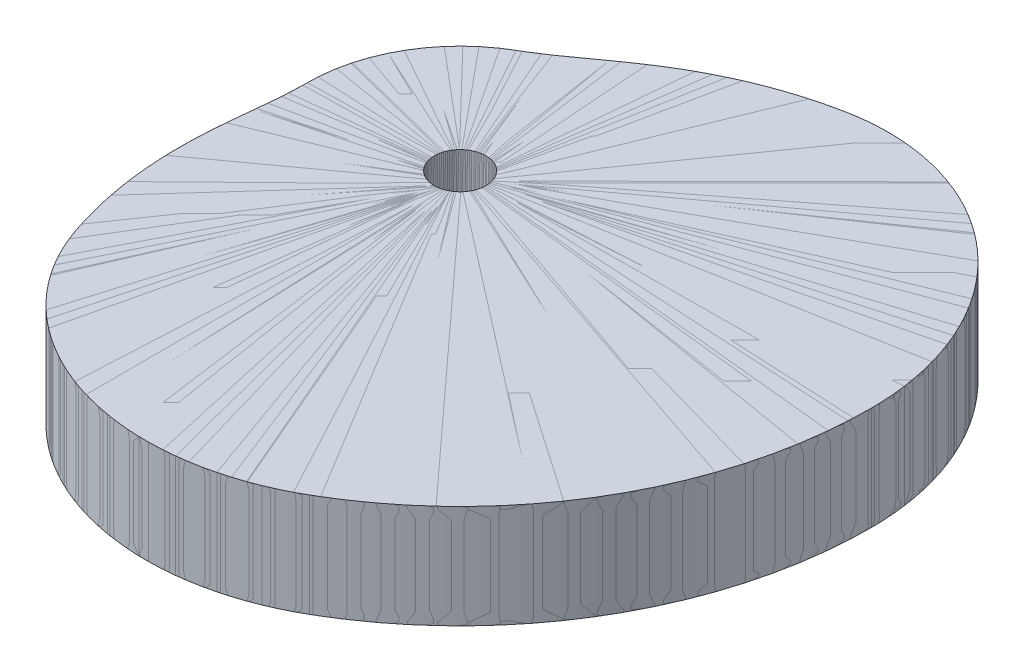
SolidWorks part; units mm, degrees
ref_plane "前视基准面" through (0, 0, 0) normal (0, 0, 1) x (1, 0, 0)
ref_plane "上视基准面" through (0, 0, 0) normal (0, 1, 0) x (1, 0, 0)
ref_plane "右视基准面" through (0, 0, 0) normal (1, 0, 0) x (0, 0, -1)
other "质心 (COM)"
other "Configuration Table"
sketch "草图1" plane through (0, 0, 0) normal (0, 0, 1) x (1, 0, 0)
  line L0 (0, -20200) -> (0, 200) construction
  line L1 (5, 0) -> (80, 0)
  line L2 (80, 0) -> (80, -20)
  line L3 (80, -20) -> (5, -20)
  line L4 (5, -20) -> (5, 0)
revolve "旋转1" add sketch "草图1" angle 360 about L0
sketch "草图2" plane through (0, 0, 0) normal (0, 1, 0) x (1, 0, 0)
  line L0 (0, 0) -> (80, 0) construction
  arc A0 (79.5, 0) -> (79.027, 6.889) centre (29.0158, -0.0054) ccw
  arc A1 (79.027, 6.889) -> (77.6192, 13.6356) centre (29.3188, 0.0363) ccw
  arc A2 (77.6192, 13.6356) -> (75.3065, 20.1004) centre (29.7814, 0.1687) ccw
  arc A3 (75.3065, 20.1004) -> (72.1392, 26.149) centre (30.4291, 0.4546) ccw
  arc A4 (72.1392, 26.149) -> (68.1863, 31.6554) centre (31.21, 0.9379) ccw
  arc A5 (68.1863, 31.6554) -> (63.5342, 36.5035) centre (32.0595, 1.6461) ccw
  arc A6 (63.5342, 36.5035) -> (58.286, 40.5905) centre (32.9058, 2.5861) ccw
  arc A7 (58.286, 40.5905) -> (52.559, 43.8282) centre (33.6758, 3.7418) ccw
  arc A8 (52.559, 43.8282) -> (46.4828, 46.1451) centre (34.3014, 5.073) ccw
  arc A9 (46.4828, 46.1451) -> (40.1976, 47.4881) centre (34.7286, 6.5165) ccw
  arc A10 (40.1976, 47.4881) -> (33.8508, 47.8241) centre (34.9248, 7.9896) ccw
  arc A11 (33.8508, 47.8241) -> (27.59, 47.1393) centre (34.8892, 9.3651) ccw
  arc A12 (27.59, 47.1393) -> (21.6911, 45.7463) centre (41.7163, -25.8693) ccw
  arc A13 (21.6911, 45.7463) -> (16.3696, 44.035) centre (41.2849, -24.3103) ccw
  arc A14 (16.3696, 44.035) -> (11.6082, 42.1045) centre (41.16, -23.9463) ccw
  arc A15 (11.6082, 42.1045) -> (7.3715, 40.0439) centre (41.8148, -25.3862) ccw
  arc A16 (7.3715, 40.0439) -> (3.6125, 37.9311) centre (44.1291, -29.7547) ccw
  arc A17 (3.6125, 37.9311) -> (0.2748, 35.8322) centre (50.161, -39.7958) ccw
  arc A18 (0.2748, 35.8322) -> (-2.7058, 33.8002) centre (66.4018, -64.3674) ccw
  arc A19 (-2.7058, 33.8002) -> (-5.3989, 31.8746) centre (130.8056, -155.763) ccw
  arc A20 (-5.3989, 31.8746) -> (-7.8774, 30.0809) centre (-573.3815, 814.0785) cw
  arc A21 (-7.8774, 30.0809) -> (-10.2149, 28.4313) centre (-88.8574, 142.3512) cw
  arc A22 (-10.2149, 28.4313) -> (-12.4833, 26.9248) centre (-53.86, 91.691) cw
  arc A23 (-12.4833, 26.9248) -> (-14.75, 25.5477) centre (-44.8377, 77.6266) cw
  arc A24 (-14.75, 25.5477) -> (-29.5, 0) centre (0, 0) ccw
  arc A25 (-29.5, 0) -> (-29.5592, -2.6515) centre (-89.6454, 0.0173) cw
  arc A26 (-29.5592, -2.6515) -> (-29.7297, -5.3693) centre (-106.3368, 0.7987) cw
  arc A27 (-29.7297, -5.3693) -> (-29.9895, -8.2184) centre (-167.7085, 5.7772) cw
  arc A28 (-29.9895, -8.2184) -> (-30.3036, -11.2617) centre (-991.7034, 89.5237) cw
  arc A29 (-30.3036, -11.2617) -> (-30.6248, -14.5568) centre (200.2976, -35.3995) ccw
  arc A30 (-30.6248, -14.5568) -> (-30.8942, -18.1541) centre (88.9447, -25.3219) ccw
  arc A31 (-30.8942, -18.1541) -> (-31.0431, -22.0941) centre (59.5447, -23.5428) ccw
  arc A32 (-31.0431, -22.0941) -> (-30.9933, -26.4058) centre (47.8328, -23.3396) ccw
  arc A33 (-30.9933, -26.4058) -> (-30.6595, -31.1053) centre (42.8925, -23.5195) ccw
  arc A34 (-30.6595, -31.1053) -> (-29.9506, -36.194) centre (41.3181, -23.6724) ccw
  arc A35 (-29.9506, -36.194) -> (-28.772, -41.6582) centre (41.6958, -23.5986) ccw
  arc A36 (-28.772, -41.6582) -> (-27.0288, -47.4633) centre (43.2617, -23.1927) ccw
  arc A37 (-27.0288, -47.4633) -> (-24.4914, -53.2277) centre (9.3342, -34.8975) ccw
  arc A38 (-24.4914, -53.2277) -> (-21.0271, -58.5562) centre (10.5432, -34.2405) ccw
  arc A39 (-21.0271, -58.5562) -> (-16.7214, -63.3279) centre (11.7208, -33.3341) ccw
  arc A40 (-16.7214, -63.3279) -> (-11.6768, -67.4315) centre (12.7573, -32.2424) ccw
  arc A41 (-11.6768, -67.4315) -> (-6.0094, -70.7724) centre (13.5974, -31.035) ccw
  arc A42 (-6.0094, -70.7724) -> (0.1541, -73.274) centre (14.2133, -29.7903) ccw
  arc A43 (0.1541, -73.274) -> (6.6788, -74.8787) centre (14.6042, -28.5873) ccw
  arc A44 (6.6788, -74.8787) -> (13.4239, -75.5489) centre (14.7927, -27.4976) ccw
  arc A45 (13.4239, -75.5489) -> (20.2458, -75.2676) centre (14.8209, -26.5797) ccw
  arc A46 (20.2458, -75.2676) -> (27.0008, -74.038) centre (14.7446, -25.8758) ccw
  arc A47 (27.0008, -74.038) -> (33.5475, -71.8839) centre (14.6279, -25.409) ccw
  arc A48 (33.5475, -71.8839) -> (39.75, -68.849) centre (14.5126, -25.1257) ccw
  arc A49 (39.75, -68.849) -> (79.5, 0) centre (0, 0) ccw
extrude "切除-拉伸1" cut sketch "草图2" along normal blind 10 and the other way blind 30 flip side to cut
sketch "草图3" plane through (0, 0, 0) normal (0, 1, 0) x (1, 0, 0)
  circle A0 centre (0, 0) radius 5 construction
  circle A1 centre (0, 0) radius 5
  arc A50 (33.5475, -71.8839) -> (39.75, -68.849) centre (14.5126, -25.1257) ccw
  arc A51 (39.75, -68.849) -> (79.5, 0) centre (0, 0) ccw
  arc A52 (79.5, 0) -> (79.027, 6.889) centre (29.0158, -0.0054) ccw
  arc A53 (79.027, 6.889) -> (77.6192, 13.6356) centre (29.3188, 0.0363) ccw
  arc A54 (77.6192, 13.6356) -> (75.3065, 20.1004) centre (29.7814, 0.1687) ccw
  arc A55 (75.3065, 20.1004) -> (72.1392, 26.149) centre (30.4291, 0.4546) ccw
  arc A56 (72.1392, 26.149) -> (68.1863, 31.6554) centre (31.21, 0.9379) ccw
  arc A57 (68.1863, 31.6554) -> (63.5342, 36.5035) centre (32.0595, 1.6461) ccw
  arc A58 (63.5342, 36.5035) -> (58.286, 40.5905) centre (32.9058, 2.5861) ccw
  arc A59 (58.286, 40.5905) -> (52.559, 43.8282) centre (33.6758, 3.7418) ccw
  arc A60 (52.559, 43.8282) -> (46.4828, 46.1451) centre (34.3014, 5.073) ccw
  arc A61 (46.4828, 46.1451) -> (40.1976, 47.4881) centre (34.7286, 6.5165) ccw
  arc A62 (40.1976, 47.4881) -> (33.8508, 47.8241) centre (34.9248, 7.9896) ccw
  arc A63 (33.8508, 47.8241) -> (27.59, 47.1393) centre (34.8892, 9.3651) ccw
  arc A64 (27.59, 47.1393) -> (21.6911, 45.7463) centre (41.7163, -25.8693) ccw
  arc A65 (21.6911, 45.7463) -> (16.3696, 44.035) centre (41.2849, -24.3103) ccw
  arc A66 (16.3696, 44.035) -> (11.6082, 42.1045) centre (41.16, -23.9463) ccw
  arc A67 (11.6082, 42.1045) -> (7.3715, 40.0439) centre (41.8148, -25.3862) ccw
  arc A68 (7.3715, 40.0439) -> (3.6125, 37.9311) centre (44.1291, -29.7547) ccw
  arc A69 (3.6125, 37.9311) -> (0.2748, 35.8322) centre (50.161, -39.7958) ccw
  arc A70 (0.2748, 35.8322) -> (-2.7058, 33.8002) centre (66.4018, -64.3674) ccw
  arc A71 (-2.7058, 33.8002) -> (-5.3989, 31.8746) centre (130.8056, -155.763) ccw
  arc A72 (-7.8774, 30.0809) -> (-5.3989, 31.8746) centre (-573.3815, 814.0785) ccw
  arc A73 (-10.2149, 28.4313) -> (-7.8774, 30.0809) centre (-88.8574, 142.3512) ccw
  arc A74 (-12.4833, 26.9248) -> (-10.2149, 28.4313) centre (-53.86, 91.691) ccw
  arc A75 (-14.75, 25.5477) -> (-12.4833, 26.9248) centre (-44.8377, 77.6266) ccw
  arc A76 (-14.75, 25.5477) -> (-29.5, 0) centre (0, 0) ccw
  arc A77 (-29.5592, -2.6515) -> (-29.5, 0) centre (-89.6454, 0.0173) ccw
  arc A78 (-29.7297, -5.3693) -> (-29.5592, -2.6515) centre (-106.3368, 0.7987) ccw
  arc A79 (-29.9895, -8.2184) -> (-29.7297, -5.3693) centre (-167.7085, 5.7772) ccw
  arc A80 (-30.3036, -11.2617) -> (-29.9895, -8.2184) centre (-991.7034, 89.5237) ccw
  arc A81 (-30.3036, -11.2617) -> (-30.6248, -14.5568) centre (200.2976, -35.3995) ccw
  arc A82 (-30.6248, -14.5568) -> (-30.8942, -18.1541) centre (88.9447, -25.3219) ccw
  arc A83 (-30.8942, -18.1541) -> (-31.0431, -22.0941) centre (59.5447, -23.5428) ccw
  arc A84 (-31.0431, -22.0941) -> (-30.9933, -26.4058) centre (47.8328, -23.3396) ccw
  arc A85 (-30.9933, -26.4058) -> (-30.6595, -31.1053) centre (42.8925, -23.5195) ccw
  arc A86 (-30.6595, -31.1053) -> (-29.9506, -36.194) centre (41.3181, -23.6724) ccw
  arc A87 (-29.9506, -36.194) -> (-28.772, -41.6582) centre (41.6958, -23.5986) ccw
  arc A88 (-28.772, -41.6582) -> (-27.0288, -47.4633) centre (43.2617, -23.1927) ccw
  arc A89 (-27.0288, -47.4633) -> (-24.4914, -53.2277) centre (9.3342, -34.8975) ccw
  arc A90 (-24.4914, -53.2277) -> (-21.0271, -58.5562) centre (10.5432, -34.2405) ccw
  arc A91 (-21.0271, -58.5562) -> (-16.7214, -63.3279) centre (11.7208, -33.3341) ccw
  arc A92 (-16.7214, -63.3279) -> (-11.6768, -67.4315) centre (12.7573, -32.2424) ccw
  arc A93 (-11.6768, -67.4315) -> (-6.0094, -70.7724) centre (13.5974, -31.035) ccw
  arc A94 (-6.0094, -70.7724) -> (0.1541, -73.274) centre (14.2133, -29.7903) ccw
  arc A95 (0.1541, -73.274) -> (6.6788, -74.8787) centre (14.6042, -28.5873) ccw
  arc A96 (6.6788, -74.8787) -> (13.4239, -75.5489) centre (14.7927, -27.4976) ccw
  arc A97 (13.4239, -75.5489) -> (20.2458, -75.2676) centre (14.8209, -26.5797) ccw
  arc A98 (20.2458, -75.2676) -> (27.0008, -74.038) centre (14.7446, -25.8758) ccw
  arc A99 (27.0008, -74.038) -> (33.5475, -71.8839) centre (14.6279, -25.409) ccw
  arc A100 (33.5475, -71.8839) -> (39.75, -68.849) centre (14.5126, -25.1257) ccw construction
  arc A101 (39.75, -68.849) -> (79.5, 0) centre (0, 0) ccw construction
  arc A102 (79.5, 0) -> (79.027, 6.889) centre (29.0158, -0.0054) ccw construction
  arc A103 (79.027, 6.889) -> (77.6192, 13.6356) centre (29.3188, 0.0363) ccw construction
  arc A104 (77.6192, 13.6356) -> (75.3065, 20.1004) centre (29.7814, 0.1687) ccw construction
  arc A105 (75.3065, 20.1004) -> (72.1392, 26.149) centre (30.4291, 0.4546) ccw construction
  arc A106 (72.1392, 26.149) -> (68.1863, 31.6554) centre (31.21, 0.9379) ccw construction
  arc A107 (68.1863, 31.6554) -> (63.5342, 36.5035) centre (32.0595, 1.6461) ccw construction
  arc A108 (63.5342, 36.5035) -> (58.286, 40.5905) centre (32.9058, 2.5861) ccw construction
  arc A109 (58.286, 40.5905) -> (52.559, 43.8282) centre (33.6758, 3.7418) ccw construction
  arc A110 (52.559, 43.8282) -> (46.4828, 46.1451) centre (34.3014, 5.073) ccw construction
  arc A111 (46.4828, 46.1451) -> (40.1976, 47.4881) centre (34.7286, 6.5165) ccw construction
  arc A112 (40.1976, 47.4881) -> (33.8508, 47.8241) centre (34.9248, 7.9896) ccw construction
  arc A113 (33.8508, 47.8241) -> (27.59, 47.1393) centre (34.8892, 9.3651) ccw construction
  arc A114 (27.59, 47.1393) -> (21.6911, 45.7463) centre (41.7163, -25.8693) ccw construction
  arc A115 (21.6911, 45.7463) -> (16.3696, 44.035) centre (41.2849, -24.3103) ccw construction
  arc A116 (16.3696, 44.035) -> (11.6082, 42.1045) centre (41.16, -23.9463) ccw construction
  arc A117 (11.6082, 42.1045) -> (7.3715, 40.0439) centre (41.8148, -25.3862) ccw construction
  arc A118 (7.3715, 40.0439) -> (3.6125, 37.9311) centre (44.1291, -29.7547) ccw construction
  arc A119 (3.6125, 37.9311) -> (0.2748, 35.8322) centre (50.161, -39.7958) ccw construction
  arc A120 (0.2748, 35.8322) -> (-2.7058, 33.8002) centre (66.4018, -64.3674) ccw construction
  arc A121 (-2.7058, 33.8002) -> (-5.3989, 31.8746) centre (130.8056, -155.763) ccw construction
  arc A122 (-7.8774, 30.0809) -> (-5.3989, 31.8746) centre (-573.3815, 814.0785) ccw construction
  arc A123 (-10.2149, 28.4313) -> (-7.8774, 30.0809) centre (-88.8574, 142.3512) ccw construction
  arc A124 (-12.4833, 26.9248) -> (-10.2149, 28.4313) centre (-53.86, 91.691) ccw construction
  arc A125 (-14.75, 25.5477) -> (-12.4833, 26.9248) centre (-44.8377, 77.6266) ccw construction
  arc A126 (-14.75, 25.5477) -> (-29.5, 0) centre (0, 0) ccw construction
  arc A127 (-29.5592, -2.6515) -> (-29.5, 0) centre (-89.6454, 0.0173) ccw construction
  arc A128 (-29.7297, -5.3693) -> (-29.5592, -2.6515) centre (-106.3368, 0.7987) ccw construction
  arc A129 (-29.9895, -8.2184) -> (-29.7297, -5.3693) centre (-167.7085, 5.7772) ccw construction
  arc A130 (-30.3036, -11.2617) -> (-29.9895, -8.2184) centre (-991.7034, 89.5237) ccw construction
  arc A131 (-30.3036, -11.2617) -> (-30.6248, -14.5568) centre (200.2976, -35.3995) ccw construction
  arc A132 (-30.6248, -14.5568) -> (-30.8942, -18.1541) centre (88.9447, -25.3219) ccw construction
  arc A133 (-30.8942, -18.1541) -> (-31.0431, -22.0941) centre (59.5447, -23.5428) ccw construction
  arc A134 (-31.0431, -22.0941) -> (-30.9933, -26.4058) centre (47.8328, -23.3396) ccw construction
  arc A135 (-30.9933, -26.4058) -> (-30.6595, -31.1053) centre (42.8925, -23.5195) ccw construction
  arc A136 (-30.6595, -31.1053) -> (-29.9506, -36.194) centre (41.3181, -23.6724) ccw construction
  arc A137 (-29.9506, -36.194) -> (-28.772, -41.6582) centre (41.6958, -23.5986) ccw construction
  arc A138 (-28.772, -41.6582) -> (-27.0288, -47.4633) centre (43.2617, -23.1927) ccw construction
  arc A139 (-27.0288, -47.4633) -> (-24.4914, -53.2277) centre (9.3342, -34.8975) ccw construction
  arc A140 (-24.4914, -53.2277) -> (-21.0271, -58.5562) centre (10.5432, -34.2405) ccw construction
  arc A141 (-21.0271, -58.5562) -> (-16.7214, -63.3279) centre (11.7208, -33.3341) ccw construction
  arc A142 (-16.7214, -63.3279) -> (-11.6768, -67.4315) centre (12.7573, -32.2424) ccw construction
  arc A143 (-11.6768, -67.4315) -> (-6.0094, -70.7724) centre (13.5974, -31.035) ccw construction
  arc A144 (-6.0094, -70.7724) -> (0.1541, -73.274) centre (14.2133, -29.7903) ccw construction
  arc A145 (0.1541, -73.274) -> (6.6788, -74.8787) centre (14.6042, -28.5873) ccw construction
  arc A146 (6.6788, -74.8787) -> (13.4239, -75.5489) centre (14.7927, -27.4976) ccw construction
  arc A147 (13.4239, -75.5489) -> (20.2458, -75.2676) centre (14.8209, -26.5797) ccw construction
  arc A148 (20.2458, -75.2676) -> (27.0008, -74.038) centre (14.7446, -25.8758) ccw construction
  arc A149 (27.0008, -74.038) -> (33.5475, -71.8839) centre (14.6279, -25.409) ccw construction
  spline S0 degree 3 poles (15.132, -75.5679) (16.2711, -75.5606) (17.4092, -75.5137) (18.5451, -75.4271) (18.7027, -75.4151) (19.0178, -75.3895) (19.4901, -75.3467) (19.8047, -75.315) (19.9619, -75.2984) (20.1833, -75.275) (20.6257, -75.2253) (21.2884, -75.1418) (21.7293, -75.0802) (21.9495, -75.0479) (23.0829, -74.8819) (24.2098, -74.6767) (25.329, -74.4328) (25.4687, -74.4023) (25.7479, -74.3402) (26.1659, -74.2434) (26.4439, -74.1765) (26.5828, -74.1424) (26.8153, -74.0854) (27.2796, -73.968) (27.9736, -73.7818) (28.4344, -73.6511) (28.6643, -73.5842) (29.7682, -73.2625) (30.8604, -72.9032) (31.9396, -72.5065) (32.2995, -72.3742) (33.0163, -72.1013) (34.0825, -71.6672) (34.7861, -71.3619) (35.1362, -71.2052) (36.1876, -70.7346) (37.2224, -70.2283) (38.2392, -69.6869) (38.4087, -69.5967) (38.7465, -69.4143) (39.2506, -69.1357) (39.5838, -68.945) (39.75, -68.849) (39.9167, -68.7528) (40.2494, -68.5591) (40.7464, -68.2649) (41.0763, -68.0663) (41.2408, -67.9665) (64.9876, -53.5574) (78.8759, -29.5022) (79.4811, -1.7324) (79.4853, -1.5399) (79.4923, -1.155) (79.4986, -0.5775) (79.5, -0.1925) (79.5, 0) (79.5, 0.192) (79.4986, 0.5759) (79.4878, 1.1517) (79.4768, 1.5355) (79.4703, 1.7273) (79.4307, 2.8786) (79.3518, 4.0279) (79.2336, 5.1738) (79.1943, 5.5553) (79.1069, 6.3173) (78.9497, 7.4577) (78.8276, 8.2149) (78.7622, 8.5928) (78.5662, 9.7257) (78.3313, 10.8513) (78.0579, 11.9681) (78.001, 12.2007) (77.8837, 12.665) (77.6979, 13.3591) (77.5675, 13.8199) (77.5006, 14.0498) (77.4607, 14.1872) (77.3796, 14.4614) (77.2545, 14.8718) (77.1687, 15.1446) (77.1252, 15.2808) (76.7769, 16.3721) (76.391, 17.4506) (75.9682, 18.5151) (75.886, 18.722) (75.7189, 19.1346) (75.4599, 19.7503) (75.2817, 20.1583) (75.1913, 20.3617) (75.127, 20.5061) (74.9972, 20.7944) (74.7982, 21.2249) (74.6627, 21.5105) (74.5943, 21.6531) (74.1014, 22.68) (73.573, 23.6891) (73.0097, 24.6792) (72.9042, 24.8646) (72.6909, 25.234) (72.3635, 25.784) (72.1406, 26.1478) (72.0279, 26.3289) (71.9408, 26.4689) (71.7652, 26.7482) (71.4973, 27.1643) (71.3159, 27.4398) (71.2245, 27.5771) (70.5978, 28.5184) (69.9383, 29.4371) (69.2468, 30.332) (69.1203, 30.4956) (68.8653, 30.8212) (68.4765, 31.3047) (68.2132, 31.6236) (68.0805, 31.7822) (67.9724, 31.9114) (67.7549, 32.1687) (67.4243, 32.551) (67.2013, 32.8035) (67.0891, 32.9291) (66.3424, 33.7652) (65.5662, 34.5741) (64.7616, 35.3547) (64.617, 35.495) (64.3261, 35.7736) (63.8843, 36.186) (63.5863, 36.457) (63.4364, 36.5916) (63.3097, 36.7054) (63.055, 36.9315) (62.6691, 37.2664) (62.4093, 37.4868) (62.2789, 37.5963) (61.4286, 38.3097) (60.5529, 38.9916) (59.653, 39.6412) (59.4937, 39.7562) (59.1736, 39.9841) (58.6889, 40.3199) (58.363, 40.5395) (58.1994, 40.6482) (58.0567, 40.7431) (57.7702, 40.9311) (57.3371, 41.2081) (57.0463, 41.3894) (56.9003, 41.4792) (55.9655, 42.0545) (55.0099, 42.5948) (54.0349, 43.0991) (53.8646, 43.1872) (53.523, 43.3611) (53.0071, 43.6154) (52.6611, 43.7804) (52.4876, 43.8617) (52.3318, 43.9348) (52.0194, 44.079) (51.5481, 44.2896) (51.2323, 44.4262) (51.074, 44.4936) (50.0755, 44.9184) (49.0616, 45.305) (48.0338, 45.6528) (47.8569, 45.7127) (47.5025, 45.8301) (46.9684, 45.9992) (46.611, 46.1073) (46.432, 46.1601) (46.2662, 46.209) (45.9342, 46.3049) (45.4342, 46.4422) (45.0998, 46.5297) (44.9323, 46.5723) (43.893, 46.8371) (42.8441, 47.0612) (41.7873, 47.2444) (41.6086, 47.2753) (41.2508, 47.3349) (40.7129, 47.4173) (40.3536, 47.4674) (40.1739, 47.4913) (40.0013, 47.5142) (39.6559, 47.5579) (39.1369, 47.6164) (38.7905, 47.651) (38.6172, 47.6671) (37.5611, 47.7654) (36.5019, 47.8214) (35.4413, 47.8352) (35.2646, 47.8375) (34.9111, 47.8397) (34.3809, 47.836) (34.0275, 47.8288) (33.8508, 47.8241) (33.6758, 47.8193) (33.3257, 47.8076) (32.8008, 47.7826) (32.4511, 47.7611) (32.2764, 47.7493) (31.2277, 47.6779) (30.1828, 47.5636) (29.1434, 47.4066) (28.9702, 47.3804) (28.6242, 47.3258) (28.1061, 47.2379) (27.762, 47.1726) (27.59, 47.1393) (27.4247, 47.1073) (27.0942, 47.0422) (26.5991, 46.9412) (26.2696, 46.8716) (26.1049, 46.8362) (25.1169, 46.6241) (24.1334, 46.3919) (23.1548, 46.1396) (22.9918, 46.0976) (22.6659, 46.0124) (22.1779, 45.8813) (21.8533, 45.7917) (21.6911, 45.7463) (21.5415, 45.7045) (21.2426, 45.6199) (20.7951, 45.4901) (20.4973, 45.4016) (20.3486, 45.3569) (19.4561, 45.0887) (18.5689, 44.8034) (17.6874, 44.5011) (17.5405, 44.4507) (17.247, 44.349) (16.8077, 44.1936) (16.5155, 44.0882) (16.3696, 44.035) (16.2355, 43.9861) (15.9675, 43.8875) (15.5665, 43.7372) (15.2998, 43.6354) (15.1666, 43.5842) (14.3672, 43.2765) (13.5735, 42.9547) (12.7855, 42.6188) (12.6542, 42.5628) (12.3919, 42.4501) (11.9994, 42.2787) (11.7385, 42.1629) (11.6082, 42.1045) (11.4888, 42.0511) (11.2501, 41.9435) (10.893, 41.7802) (10.6555, 41.6701) (10.5369, 41.6148) (9.8252, 41.2825) (9.1189, 40.939) (8.4182, 40.5843) (8.3014, 40.5252) (8.0682, 40.4063) (7.7192, 40.2263) (7.4873, 40.1049) (7.3715, 40.0439) (7.2655, 39.9881) (7.0538, 39.8759) (6.7369, 39.7063) (6.5262, 39.5923) (6.421, 39.535) (5.7896, 39.1914) (5.163, 38.8392) (4.5413, 38.4785) (4.4377, 38.4184) (4.2307, 38.2977) (3.9211, 38.1153) (3.7153, 37.9927) (3.6125, 37.9311) (3.5185, 37.8748) (3.3308, 37.7619) (3.0498, 37.5916) (2.8629, 37.4773) (2.7695, 37.42) (2.2094, 37.0763) (1.6531, 36.7264) (1.1006, 36.3705) (1.0085, 36.3112) (0.8245, 36.1923) (0.5492, 36.013) (0.3662, 35.8926) (0.2748, 35.8322) (0.1911, 35.777) (0.024, 35.6664) (-0.2263, 35.4999) (-0.3929, 35.3885) (-0.4761, 35.3326) (-0.9754, 34.9977) (-1.4722, 34.659) (-1.9664, 34.3166) (-2.0488, 34.2596) (-2.2134, 34.1452) (-2.46, 33.9732) (-2.6239, 33.8579) (-2.7058, 33.8002) (-2.781, 33.7473) (-2.9313, 33.6413) (-3.1566, 33.482) (-3.3067, 33.3757) (-3.3817, 33.3224) (-3.8317, 33.0031) (-4.2805, 32.6821) (-4.7282, 32.3596) (-4.8718, 32.2562) (-5.1587, 32.049) (-5.5883, 31.7371) (-5.8747, 31.5293) (-6.018, 31.4254) (-6.4308, 31.1261) (-6.8439, 30.8272) (-7.2572, 30.5286) (-7.3261, 30.4788) (-7.4639, 30.3793) (-7.6706, 30.23) (-7.8085, 30.1306) (-7.8774, 30.0809) (-7.9418, 30.0344) (-8.0708, 29.9414) (-8.2646, 29.8025) (-8.3939, 29.7101) (-8.4586, 29.6639) (-8.8467, 29.387) (-9.2363, 29.1121) (-9.6273, 28.8391) (-9.6925, 28.7936) (-9.8229, 28.7028) (-10.0188, 28.5668) (-10.1495, 28.4764) (-10.2149, 28.4313) (-10.2772, 28.3883) (-10.4017, 28.3025) (-10.5892, 28.1745) (-10.7143, 28.0895) (-10.777, 28.0471) (-11.1528, 27.7927) (-11.5309, 27.5416) (-11.9112, 27.2939) (-11.9746, 27.2526) (-12.1015, 27.1702) (-12.2922, 27.0472) (-12.4196, 26.9656) (-12.4833, 26.9248) (-12.5454, 26.8852) (-12.6697, 26.806) (-12.8568, 26.6883) (-12.9817, 26.6102) (-13.0443, 26.5712) (-13.4195, 26.3375) (-13.7973, 26.108) (-14.1777, 25.8826) (-14.3046, 25.8074) (-14.5591, 25.6579) (-14.9427, 25.4368) (-15.196, 25.2854) (-15.3221, 25.2088) (-24.1155, 19.8641) (-29.2606, 10.9525) (-29.4925, 0.6649) (-29.4958, 0.5174) (-29.5003, 0.2223) (-29.4999, -0.2204) (-29.5022, -0.5155) (-29.5038, -0.6631) (-29.5088, -1.1051) (-29.5187, -1.5471) (-29.5335, -1.9889) (-29.5359, -2.0626) (-29.5411, -2.2098) (-29.5495, -2.4307) (-29.5559, -2.5779) (-29.5592, -2.6515) (-29.5626, -2.7271) (-29.5696, -2.8782) (-29.5808, -3.1049) (-29.5887, -3.256) (-29.5928, -3.3315) (-29.6172, -3.7847) (-29.6456, -4.2377) (-29.678, -4.6904) (-29.6834, -4.7659) (-29.6945, -4.9168) (-29.7115, -5.1431) (-29.7236, -5.2939) (-29.7297, -5.3693) (-29.7361, -5.4485) (-29.749, -5.6069) (-29.7688, -5.8445) (-29.7823, -6.0029) (-29.7891, -6.0821) (-29.8299, -6.5571) (-29.8732, -7.032) (-29.919, -7.5066) (-29.9266, -7.5858) (-29.942, -7.7439) (-29.9654, -7.9812) (-29.9814, -8.1394) (-29.9895, -8.2184) (-29.9981, -8.303) (-30.0153, -8.4721) (-30.0412, -8.7257) (-30.0585, -8.8948) (-30.0671, -8.9793) (-30.1191, -9.4866) (-30.1714, -9.9938) (-30.2242, -10.501) (-30.2425, -10.677) (-30.2792, -11.0289) (-30.3346, -11.5569) (-30.3705, -11.909) (-30.3883, -12.085) (-30.4438, -12.634) (-30.4974, -13.1832) (-30.5489, -13.7326) (-30.5575, -13.8242) (-30.5746, -14.0073) (-30.5999, -14.282) (-30.6165, -14.4652) (-30.6248, -14.5568) (-30.6338, -14.6566) (-30.6517, -14.8562) (-30.6773, -15.1557) (-30.6941, -15.3555) (-30.7023, -15.4553) (-30.7517, -16.0545) (-30.7966, -16.6541) (-30.837, -17.254) (-30.8438, -17.354) (-30.857, -17.554) (-30.876, -17.854) (-30.8883, -18.054) (-30.8942, -18.1541) (-30.9008, -18.2634) (-30.9136, -18.4821) (-30.9312, -18.8102) (-30.9422, -19.029) (-30.9475, -19.1384) (-30.9795, -19.7948) (-31.0043, -20.4515) (-31.0219, -21.1085) (-31.0249, -21.218) (-31.0304, -21.437) (-31.0374, -21.7655) (-31.0413, -21.9845) (-31.0431, -22.0941) (-31.045, -22.2138) (-31.0483, -22.4534) (-31.0514, -22.8128) (-31.0525, -23.0524) (-31.0527, -23.1722) (-31.0542, -23.8909) (-31.0459, -24.6097) (-31.0278, -25.3282) (-31.0248, -25.448) (-31.0182, -25.6875) (-31.0067, -26.0467) (-30.9979, -26.2861) (-30.9933, -26.4058) (-30.9882, -26.5366) (-30.9774, -26.7982) (-30.9588, -27.1904) (-30.9451, -27.4518) (-30.9379, -27.5825) (-30.8948, -28.3667) (-30.8391, -29.1501) (-30.771, -29.9326) (-30.7597, -30.063) (-30.7363, -30.3237) (-30.6991, -30.7146) (-30.6729, -30.9751) (-30.6595, -31.1053) (-30.6448, -31.2473) (-30.6147, -31.5312) (-30.5669, -31.9568) (-30.5334, -32.2403) (-30.5162, -32.382) (-30.4131, -33.2323) (-30.2949, -34.0806) (-30.1617, -34.9267) (-30.1395, -35.0677) (-30.0943, -35.3496) (-30.0239, -35.7721) (-29.9753, -36.0534) (-29.9506, -36.194) (-29.9237, -36.347) (-29.869, -36.6527) (-29.7839, -37.1108) (-29.7252, -37.4159) (-29.6954, -37.5683) (-29.5164, -38.4829) (-29.3199, -39.3938) (-29.106, -40.3009) (-29.0703, -40.452) (-28.998, -40.7541) (-28.8867, -41.2066) (-28.8105, -41.5077) (-28.772, -41.6582) (-28.7301, -41.8213) (-28.6454, -42.1473) (-28.515, -42.6354) (-28.4258, -42.9602) (-28.3807, -43.1225) (-28.1098, -44.0961) (-27.8192, -45.0639) (-27.5089, -46.0257) (-27.4572, -46.1859) (-27.3527, -46.5061) (-27.1927, -46.9854) (-27.0838, -47.3041) (-27.0288, -47.4633) (-26.9717, -47.6289) (-26.8562, -47.9595) (-26.6732, -48.4522) (-26.5476, -48.7792) (-26.4836, -48.9422) (-26.0999, -49.9208) (-25.6764, -50.8829) (-25.2139, -51.8268) (-25.1368, -51.9841) (-24.9805, -52.2976) (-24.7398, -52.7647) (-24.5749, -53.0737) (-24.4914, -53.2277) (-24.4072, -53.3831) (-24.2368, -53.6927) (-23.9748, -54.1538) (-23.7962, -54.4588) (-23.7058, -54.6106) (-23.1636, -55.5223) (-22.5855, -56.4115) (-21.9723, -57.277) (-21.8717, -57.4191) (-21.6686, -57.7018) (-21.3584, -58.122) (-21.1479, -58.3993) (-21.0418, -58.5372) (-20.9312, -58.681) (-20.7081, -58.967) (-20.3678, -59.3917) (-20.1373, -59.6718) (-20.0212, -59.8111) (-19.3342, -60.6347) (-18.6156, -61.431) (-17.8666, -62.1987) (-17.746, -62.3224) (-17.5031, -62.5683) (-17.1341, -62.9326) (-16.8851, -63.1722) (-16.7599, -63.2913) (-16.6245, -63.4199) (-16.3523, -63.6754) (-15.9388, -64.0534) (-15.6599, -64.3017) (-15.5196, -64.4249) (-14.7045, -65.1411) (-13.8627, -65.8259) (-12.9955, -66.4782) (-12.858, -66.5816) (-12.5818, -66.7868) (-12.1638, -67.0897) (-11.8827, -67.2881) (-11.7416, -67.3864) (-11.5843, -67.496) (-11.2684, -67.7132) (-10.7903, -68.0328) (-10.4689, -68.2417) (-10.3075, -68.3451) (-9.3832, -68.9373) (-8.4376, -69.4948) (-7.4719, -70.0167) (-7.3211, -70.0982) (-7.0187, -70.2594) (-6.5623, -70.496) (-6.2562, -70.6501) (-6.1027, -70.7262) (-5.9267, -70.8136) (-5.5736, -70.986) (-5.0405, -71.2379) (-4.683, -71.4011) (-4.5037, -71.4816) (-3.4912, -71.9362) (-2.4628, -72.3536) (-1.4199, -72.7332) (-1.2599, -72.7915) (-0.9392, -72.9062) (-0.4561, -73.073) (-0.1329, -73.1805) (0.029, -73.2333) (0.2205, -73.2959) (0.6042, -73.4184) (1.1822, -73.5948) (1.569, -73.7075) (1.7627, -73.7625) (2.841, -74.0691) (3.9296, -74.3368) (5.0271, -74.5654) (5.192, -74.5998) (5.5222, -74.6667) (6.0186, -74.7618) (6.3501, -74.8215) (6.5161, -74.8506) (6.7198, -74.8862) (7.1276, -74.9547) (7.7408, -75.0497) (8.1502, -75.1077) (8.3551, -75.1354) (9.4758, -75.2869) (10.6012, -75.3987) (11.7298, -75.4708) (11.8944, -75.4813) (12.2237, -75.5006) (12.718, -75.5245) (13.0476, -75.537) (13.2125, -75.5425) (13.4257, -75.5495) (13.8521, -75.5607) (14.4921, -75.5692) (14.9187, -75.5692) (15.132, -75.5679) (16.2711, -75.5606) (17.4092, -75.5137) knots -0.001752 0 0 0 0.009351 0.009351 0.009351 0.01065 0.011948 0.013246 0.013246 0.013246 0.015074 0.016902 0.01873 0.01873 0.01873 0.028134 0.028134 0.028134 0.029308 0.030482 0.031657 0.031657 0.031657 0.033623 0.03559 0.037556 0.037556 0.037556 0.046996 0.046996 0.046996 0.050145 0.053294 0.056444 0.056444 0.056444 0.065901 0.065901 0.065901 0.067477 0.069054 0.07063 0.07063 0.07063 0.072211 0.073792 0.075373 0.075373 0.075373 0.284742 0.284742 0.284742 0.286323 0.287904 0.289485 0.289485 0.289485 0.291061 0.292638 0.294214 0.294214 0.294214 0.303672 0.303672 0.303672 0.306821 0.30997 0.31312 0.31312 0.31312 0.322559 0.322559 0.322559 0.324525 0.326492 0.328458 0.328458 0.328458 0.329633 0.330807 0.331981 0.331981 0.331981 0.341385 0.341385 0.341385 0.343213 0.345041 0.346869 0.346869 0.346869 0.348167 0.349466 0.350764 0.350764 0.350764 0.360115 0.360115 0.360115 0.361867 0.363619 0.365371 0.365371 0.365371 0.366725 0.36808 0.369434 0.369434 0.369434 0.378718 0.378718 0.378718 0.380416 0.382114 0.383813 0.383813 0.383813 0.385196 0.386579 0.387963 0.387963 0.387963 0.397166 0.397166 0.397166 0.39882 0.400474 0.402128 0.402128 0.402128 0.403527 0.404925 0.406324 0.406324 0.406324 0.415435 0.415435 0.415435 0.417049 0.418662 0.420276 0.420276 0.420276 0.421683 0.42309 0.424497 0.424497 0.424497 0.433509 0.433509 0.433509 0.435083 0.436657 0.438231 0.438231 0.438231 0.439644 0.441057 0.44247 0.44247 0.44247 0.451377 0.451377 0.451377 0.45291 0.454443 0.455977 0.455977 0.455977 0.457396 0.458815 0.460234 0.460234 0.460234 0.469038 0.469038 0.469038 0.470528 0.472017 0.473507 0.473507 0.473507 0.474936 0.476366 0.477795 0.477795 0.477795 0.486501 0.486501 0.486501 0.487953 0.489404 0.490856 0.490856 0.490856 0.492294 0.493732 0.49517 0.49517 0.49517 0.503798 0.503798 0.503798 0.505237 0.506675 0.508113 0.508113 0.508113 0.509496 0.510879 0.512263 0.512263 0.512263 0.520561 0.520561 0.520561 0.521944 0.523327 0.52471 0.52471 0.52471 0.525986 0.527261 0.528537 0.528537 0.528537 0.536189 0.536189 0.536189 0.537465 0.53874 0.540016 0.540016 0.540016 0.541188 0.54236 0.543533 0.543533 0.543533 0.550566 0.550566 0.550566 0.551739 0.552911 0.554083 0.554083 0.554083 0.555158 0.556233 0.557308 0.557308 0.557308 0.563758 0.563758 0.563758 0.564833 0.565908 0.566983 0.566983 0.566983 0.567966 0.56895 0.569934 0.569934 0.569934 0.575837 0.575837 0.575837 0.576821 0.577804 0.578788 0.578788 0.578788 0.579688 0.580587 0.581487 0.581487 0.581487 0.586884 0.586884 0.586884 0.587784 0.588683 0.589583 0.589583 0.589583 0.590406 0.591229 0.592052 0.592052 0.592052 0.596989 0.596989 0.596989 0.597812 0.598635 0.599458 0.599458 0.599458 0.600214 0.600969 0.601724 0.601724 0.601724 0.606256 0.606256 0.606256 0.607709 0.609162 0.610615 0.610615 0.610615 0.614803 0.614803 0.614803 0.615501 0.616199 0.616897 0.616897 0.616897 0.61755 0.618202 0.618855 0.618855 0.618855 0.622771 0.622771 0.622771 0.623424 0.624076 0.624729 0.624729 0.624729 0.62535 0.625972 0.626593 0.626593 0.626593 0.63032 0.63032 0.63032 0.630941 0.631563 0.632184 0.632184 0.632184 0.632789 0.633394 0.633999 0.633999 0.633999 0.63763 0.63763 0.63763 0.638842 0.640054 0.641265 0.641265 0.641265 0.71885 0.71885 0.71885 0.720062 0.721274 0.722485 0.722485 0.722485 0.726116 0.726116 0.726116 0.726721 0.727326 0.727931 0.727931 0.727931 0.728552 0.729174 0.729795 0.729795 0.729795 0.733522 0.733522 0.733522 0.734144 0.734765 0.735386 0.735386 0.735386 0.736039 0.736691 0.737344 0.737344 0.737344 0.74126 0.74126 0.74126 0.741913 0.742566 0.743218 0.743218 0.743218 0.743916 0.744614 0.745312 0.745312 0.745312 0.7495 0.7495 0.7495 0.750953 0.752406 0.753859 0.753859 0.753859 0.758391 0.758391 0.758391 0.759146 0.759902 0.760657 0.760657 0.760657 0.76148 0.762303 0.763126 0.763126 0.763126 0.768064 0.768064 0.768064 0.768887 0.76971 0.770533 0.770533 0.770533 0.771432 0.772332 0.773231 0.773231 0.773231 0.778628 0.778628 0.778628 0.779528 0.780427 0.781327 0.781327 0.781327 0.782311 0.783295 0.784278 0.784278 0.784278 0.790181 0.790181 0.790181 0.791165 0.792149 0.793133 0.793133 0.793133 0.794208 0.795283 0.796358 0.796358 0.796358 0.802807 0.802807 0.802807 0.803882 0.804957 0.806032 0.806032 0.806032 0.807204 0.808377 0.809549 0.809549 0.809549 0.816583 0.816583 0.816583 0.817755 0.818927 0.820099 0.820099 0.820099 0.821375 0.82265 0.823926 0.823926 0.823926 0.831579 0.831579 0.831579 0.832854 0.83413 0.835405 0.835405 0.835405 0.836788 0.838171 0.839554 0.839554 0.839554 0.847853 0.847853 0.847853 0.849236 0.850619 0.852002 0.852002 0.852002 0.85344 0.854879 0.856317 0.856317 0.856317 0.864945 0.864945 0.864945 0.866383 0.867821 0.86926 0.86926 0.86926 0.870711 0.872162 0.873614 0.873614 0.873614 0.88232 0.88232 0.88232 0.88375 0.885179 0.886609 0.886609 0.886609 0.888098 0.889588 0.891077 0.891077 0.891077 0.899881 0.899881 0.899881 0.9013 0.902719 0.904139 0.904139 0.904139 0.905672 0.907205 0.908738 0.908738 0.908738 0.917646 0.917646 0.917646 0.919059 0.920471 0.921884 0.921884 0.921884 0.923458 0.925032 0.926607 0.926607 0.926607 0.935618 0.935618 0.935618 0.937025 0.938432 0.939839 0.939839 0.939839 0.941453 0.943067 0.94468 0.94468 0.94468 0.953791 0.953791 0.953791 0.95519 0.956589 0.957987 0.957987 0.957987 0.959641 0.961296 0.96295 0.96295 0.96295 0.972153 0.972153 0.972153 0.973536 0.974919 0.976303 0.976303 0.976303 0.978001 0.979699 0.981397 0.981397 0.981397 0.990681 0.990681 0.990681 0.992036 0.99339 0.994745 0.994745 0.994745 0.996496 0.998248 1 1 1 1.009351 1.009351 1.009351 weights 1 0.999595 0.999595 1 1 1 1 1 1 1 1 1 1 1 0.999602 0.999602 1 1 1 1 1 1 1 1 1 1 1 0.999606 0.999606 1 1 1 1 1 1 0.99961 0.99961 1 1 1 1 1 1 1 1 1 1 1 0.91781 0.91781 1 1 1 1 1 1 1 1 1 1 1 0.99961 0.99961 1 1 1 1 1 1 0.999606 0.999606 1 1 1 1 1 1 1 1 1 1 1 0.999602 0.999602 1 1 1 1 1 1 1 1 1 1 1 0.999595 0.999595 1 1 1 1 1 1 1 1 1 1 1 0.999585 0.999585 1 1 1 1 1 1 1 1 1 1 1 0.999573 0.999573 1 1 1 1 1 1 1 1 1 1 1 0.999558 0.999558 1 1 1 1 1 1 1 1 1 1 1 0.99954 0.99954 1 1 1 1 1 1 1 1 1 1 1 0.999519 0.999519 1 1 1 1 1 1 1 1 1 1 1 0.999495 0.999495 1 1 1 1 1 1 1 1 1 1 1 0.999469 0.999469 1 1 1 1 1 1 1 1 1 1 1 0.999441 0.999441 1 1 1 1 1 1 1 1 1 1 1 0.999862 0.999862 1 1 1 1 1 1 1 1 1 1 1 0.999877 0.999877 1 1 1 1 1 1 1 1 1 1 1 0.999895 0.999895 1 1 1 1 1 1 1 1 1 1 1 0.999915 0.999915 1 1 1 1 1 1 1 1 1 1 1 0.999938 0.999938 1 1 1 1 1 1 1 1 1 1 1 0.999961 0.999961 1 1 1 1 1 1 1 1 1 1 1 0.999981 0.999981 1 1 1 1 1 1 1 1 1 1 1 0.999996 0.999996 1 1 1 1 1 1 1 1 1 1 1 1 1 1 1 1 1 1 1 0.999991 0.999991 1 1 1 1 1 1 1 1 1 1 1 0.999974 0.999974 1 1 1 1 1 1 1 1 1 1 1 0.999959 0.999959 1 1 1 1 1 1 0.91805 0.91805 1 1 1 1 1 1 0.999959 0.999959 1 1 1 1 1 1 1 1 1 1 1 0.999974 0.999974 1 1 1 1 1 1 1 1 1 1 1 0.999991 0.999991 1 1 1 1 1 1 1 1 1 1 1 1 1 1 1 1 1 1 1 0.999996 0.999996 1 1 1 1 1 1 1 1 1 1 1 0.999981 0.999981 1 1 1 1 1 1 1 1 1 1 1 0.999961 0.999961 1 1 1 1 1 1 1 1 1 1 1 0.999938 0.999938 1 1 1 1 1 1 1 1 1 1 1 0.999915 0.999915 1 1 1 1 1 1 1 1 1 1 1 0.999895 0.999895 1 1 1 1 1 1 1 1 1 1 1 0.999877 0.999877 1 1 1 1 1 1 1 1 1 1 1 0.999862 0.999862 1 1 1 1 1 1 1 1 1 1 1 0.999441 0.999441 1 1 1 1 1 1 1 1 1 1 1 0.999469 0.999469 1 1 1 1 1 1 1 1 1 1 1 0.999495 0.999495 1 1 1 1 1 1 1 1 1 1 1 0.999519 0.999519 1 1 1 1 1 1 1 1 1 1 1 0.99954 0.99954 1 1 1 1 1 1 1 1 1 1 1 0.999558 0.999558 1 1 1 1 1 1 1 1 1 1 1 0.999573 0.999573 1 1 1 1 1 1 1 1 1 1 1 0.999585 0.999585 1 1 1 1 1 1 1 1 1 1 1 0.999595 0.999595 only from (15.132, -75.5679) to (15.132, -75.5679)
  dimension "D1" = 0
extrude "凸台-拉伸1" add sketch "草图3" against normal up to surface (20 mm away) separate body up to face at (0, -20, -5)
sketch "草图4" plane through (0, 0, 0) normal (0, 1, 0) x (1, 0, 0)
  circle A0 centre (0, 0) radius 5
sketch "草图5" plane through (0, -20, 0) normal (0, -1, 0) x (1, 0, 0)
  circle A0 centre (0, 0) radius 5
